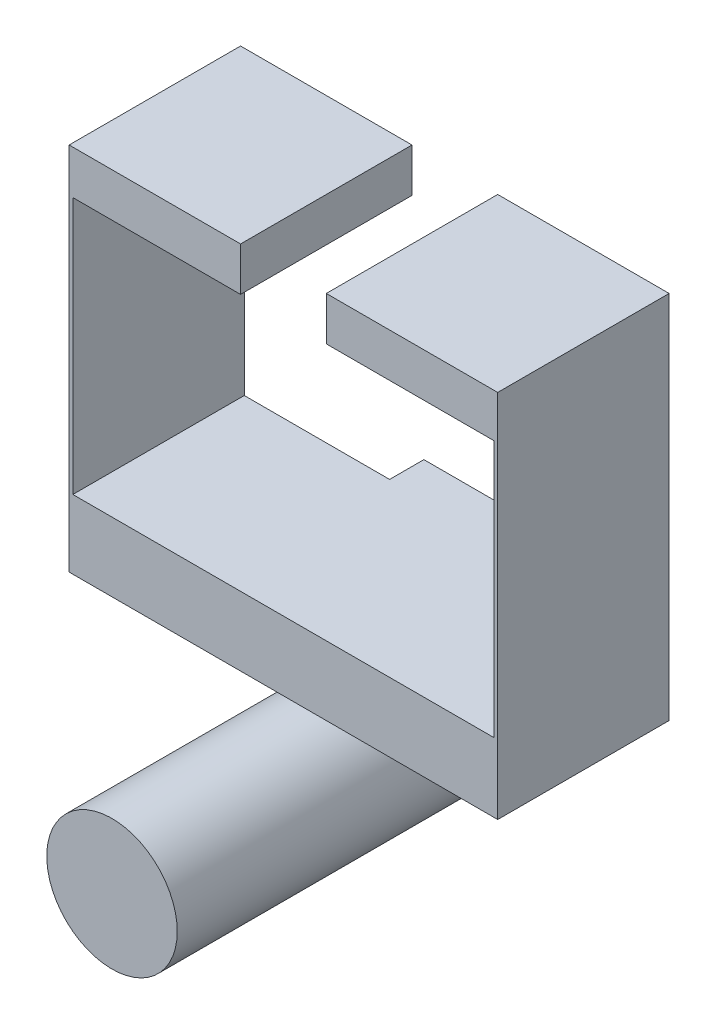
SolidWorks part; units mm, degrees
material "Titanium"
ref_plane "Front Plane" through (0, 0, 0) normal (0, 0, 1) x (1, 0, 0)
ref_plane "Top Plane" through (0, 0, 0) normal (0, 1, 0) x (1, 0, 0)
ref_plane "Right Plane" through (0, 0, 0) normal (1, 0, 0) x (0, 0, -1)
sketch "Sketch1" plane through (0, 0, 0) normal (0, 0, 1) x (1, 0, 0)
  circle A0 centre (0, 0) radius 9.6672
  dimension "D1" = 19.3344
extrude "Boss-Extrude1" add sketch "Sketch1" along normal blind 50.8
sketch "Sketch2" plane through (0, 0, 0) normal (0, 0, -1) x (-1, 0, 0)
  line L0 (9.6672, 0) -> (9.6672, 12.7)
  line L1 (9.6672, 12.7) -> (-9.6672, 12.7)
  line L2 (-9.6672, 12.7) -> (-9.6672, 0)
  line L3 (-9.6672, 0) -> (9.6672, 0)
  circle A1 centre (0, 0) radius 9.6672 construction
  dimension "D1" = 12.7
extrude "Boss-Extrude2" add sketch "Sketch2" against normal blind 8.89
sketch "Sketch4" plane through (0, 0, 0) normal (0, 0, -1) x (-1, 0, 0)
  line L0 (-31.75, 12.7) -> (-31.75, 22.9352)
  line L2 (-31.75, 22.9352) -> (31.75, 22.9352)
  line L3 (31.75, 22.9352) -> (31.75, 12.7)
  line L4 (-31.75, 12.7) -> (-9.6672, 12.7)
  line L5 (9.6672, 12.7) -> (31.75, 12.7)
  line L6 (-9.6672, 12.7) -> (9.6672, 12.7)
  dimension "D1" = 63.5
  dimension "D2" = 10.2352
extrude "Boss-Extrude3" add sketch "Sketch4" against normal blind 25.4
sketch "Sketch5" plane through (0, 0, 0) normal (0, 0, -1) x (-1, 0, 0)
  line L0 (0, 0) -> (0, 44.2128) construction
  line L2 (31.75, 22.9352) -> (31.2001, 22.9352)
  line L3 (31.75, 22.9352) -> (31.75, 61.0352)
  line L4 (31.75, 61.0352) -> (31.2001, 61.0352)
  line L5 (31.2001, 22.9352) -> (31.2001, 61.0352)
  line L6 (-31.75, 22.9352) -> (-31.2001, 22.9352)
  line L7 (-31.75, 22.9352) -> (-31.75, 61.0352)
  line L8 (-31.75, 61.0352) -> (-31.2001, 61.0352)
  line L9 (-31.2001, 22.9352) -> (-31.2001, 61.0352)
  dimension "D1" = 38.1
  dimension "D2" = 0.5499
extrude "Boss-Extrude4" add sketch "Sketch5" against normal blind 25.4
sketch "Sketch6" plane through (0, 0, 0) normal (0, 0, -1) x (-1, 0, 0)
  line L1 (31.75, 61.0352) -> (6.35, 61.0352)
  line L2 (31.75, 61.0352) -> (31.75, 67.5085)
  line L3 (31.75, 67.5085) -> (6.35, 67.5085)
  line L4 (6.35, 61.0352) -> (6.35, 67.5085)
  line L5 (-31.75, 61.0352) -> (-6.35, 61.0352)
  line L6 (-31.75, 61.0352) -> (-31.75, 67.5085)
  line L7 (-31.75, 67.5085) -> (-6.35, 67.5085)
  line L8 (-6.35, 61.0352) -> (-6.35, 67.5085)
  dimension "D1" = 6.4733
  dimension "D2" = 25.4
extrude "Boss-Extrude5" add sketch "Sketch6" against normal blind 25.4
sketch "Sketch7" plane through (0, 0, 0) normal (0, 0, -1) x (-1, 0, 0)
  line L0 (-31.75, 12.7) -> (-9.6672, 0)
  line L1 (-9.6672, 0) -> (-9.6672, 2.54)
  line L2 (-9.6672, 12.7) -> (-9.6672, 0) construction
  line L3 (-9.6672, 2.54) -> (-29.21, 12.7)
  line L4 (-31.75, 12.7) -> (-9.6672, 12.7) construction
  line L5 (-29.21, 12.7) -> (-31.75, 12.7)
  line L6 (9.6672, 0) -> (31.75, 12.7)
  line L7 (31.75, 12.7) -> (29.21, 12.7)
  line L8 (9.6672, 12.7) -> (31.75, 12.7) construction
  line L9 (29.21, 12.7) -> (9.6672, 2.54)
  line L10 (9.6672, 0) -> (9.6672, 12.7) construction
  line L11 (9.6672, 2.54) -> (9.6672, 0)
  dimension "D1" = 2.54
extrude "Boss-Extrude6" add sketch "Sketch7" against normal blind 8.89
sketch "Sketch12" plane through (0, 0, 0) normal (0, 0, -1) x (-1, 0, 0)
  line L0 (-9.6672, 22.9352) -> (-9.6672, 2.54)
  line L1 (31.2001, 22.9352) -> (-31.2001, 22.9352) construction
  line L2 (9.6672, 12.7) -> (9.6672, 22.9352)
  line L3 (9.6672, 22.9352) -> (-9.6672, 22.9352)
sketch "Sketch14" plane through (0, 0, 0) normal (0, 0, -1) x (-1, 0, 0)
  line L1 (31.2001, 22.9352) -> (-31.2001, 22.9352) construction
  line L3 (9.6672, 22.9352) -> (-9.6672, 22.9352)
  line L4 (-9.6672, 22.9352) -> (-9.6672, 0)
  line L5 (9.6672, 22.9352) -> (9.6672, 0)
  arc A1 (-9.6672, 0) -> (9.6672, 0) centre (0, 0) ccw
extrude "Boss-Extrude7" add sketch "Sketch14" along normal blind 5.08
equation "\"SF\"= 4"
equation "\"W\"= 1300"
equation "\"F\"= 650"
equation "\"L1\"= 2in"
equation "\"SY\"= 120091"
equation "\"E\"= 16534300"
equation "\"z\"= ( \"SF\" * \"W\" * \"L1\" ) / ( 2 * \"SY\" )"
equation "\"r1\"= ( 4 * ( \"z\" / pi ) ) ^ ( 1 / 3 )"
equation "\"d1\"= 2 * \"r1\""
equation "\"L2\"= .5in"
equation "\"T2\"= ( \"W\" * \"SF\" ) / ( \"d1\" * \"SY\" )"
equation "\"L3\"= 2.5in"
equation "\"b3\"= 1in"
equation "\"T3\"= ( ( 1.5 * \"L3\" * \"W\" * \"SF\" ) / ( \"b3\" * \"SY\" ) ) ^ ( 1 / 2 )"
equation "\"T4\"= 1.5in"
equation "\"W4\"= 1in"
equation "\"L4\"= ( \"F\" * \"SF\" ) / ( \"W4\" * \"SY\" )"
equation "\"W5\"= 1in"
equation "\"L5\"= 1in"
equation "\"T5\"= ( ( 1.5 * \"W\" * \"L5\" * \"SF\" ) / ( \"W5\" * \"SY\" ) ) ^ ( 1 / 2 )"
equation "\"D1@Sketch1\"= \"d1\""
equation "\"D1@Boss-Extrude1\"=\"L1\""
equation "\"D1@Sketch2\"=\"L2\""
equation "\"D1@Boss-Extrude2\"=.35"
equation "\"D1@Sketch4\"= \"L3\""
equation "\"D2@Sketch4\"= \"T3\""
equation "\"W3\"= 1in"
equation "\"D1@Boss-Extrude3\"=\"W3\""
equation "\"D1@Sketch5\"= \"T4\""
equation "\"D2@Sketch5\"= \"L4\""
equation "\"D1@Boss-Extrude4\"=\"W4\""
equation "\"D1@Sketch6\"= \"T5\""
equation "\"D2@Sketch6\"= \"L5\""
equation "\"D1@Boss-Extrude5\"= \"W5\""
